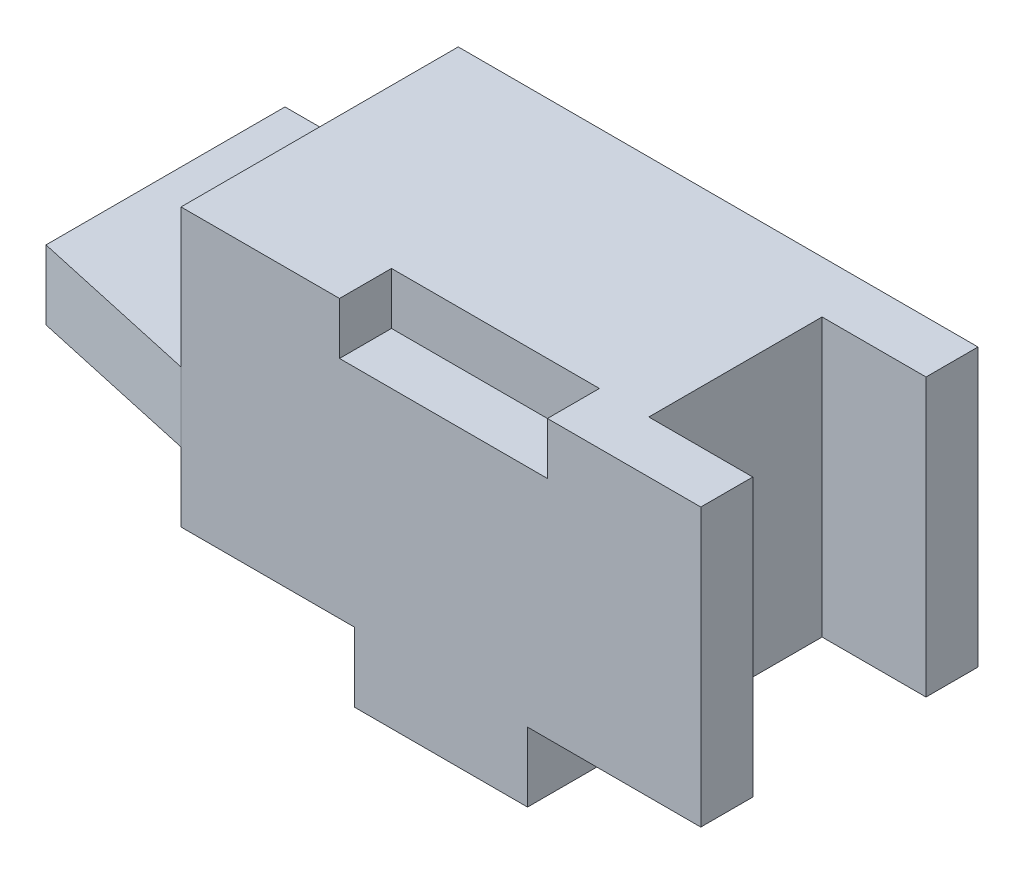
SolidWorks part; units mm, degrees
ref_plane "Спереди" through (0, 0, 0) normal (0, 0, 1) x (1, 0, 0)
ref_plane "Сверху" through (0, 0, 0) normal (0, 1, 0) x (1, 0, 0)
ref_plane "Справа" through (0, 0, 0) normal (1, 0, 0) x (0, 0, -1)
sketch "Эскиз1" plane through (0, 0, 0) normal (0, 0, 1) x (1, 0, 0)
  line L1 (150, -80) -> (0, -80)
  line L2 (150, -80) -> (150, 0)
  line L3 (150, 0) -> (0, 0)
  line L10 (50, -80) -> (50, -100)
  line L11 (50, -100) -> (100, -100)
  line L12 (100, -80) -> (100, -100)
  line L13 (0, -80) -> (0, 0)
  point P0 (0, 0)
  dimension "D1" = 150
  dimension "D2" = 80
  dimension "D7" = 50
  dimension "D8" = 150
  dimension "D9" = 50
  dimension "D10" = 20
extrude "Бобышка-Вытянуть3" add sketch "Эскиз1" along normal blind 80 contours L12 L1 L10 L11 | L13 L1 L2 L3
sketch "Эскиз3" plane through (0, 0, 0) normal (-1, 0, 0) x (0, 0, 1)
  line L0 (0, -80) -> (0, 0) construction
  line L1 (0, -60) -> (80, -60)
  line L2 (0, -60) -> (0, -40)
  line L3 (0, -40) -> (80, -40)
  line L4 (80, -60) -> (80, -40)
  line L5 (80, -80) -> (80, 0) construction
  dimension "D1" = 20
extrude "Бобышка-Вытянуть4" add sketch "Эскиз3" along normal blind 50
sketch "Эскиз4" plane through (0, -60, 0) normal (0, -1, 0) x (1, 0, 0)
  line L0 (-50, 68.9679) -> (0, 80)
  line L1 (-50, 0) -> (-50, 80) construction
  line L2 (-50, 80) -> (0, 80) construction
  line L3 (0, 80) -> (0, 0) construction
  line L4 (0, 80) -> (-50, 80)
  line L5 (-50, 80) -> (-50, 70.9811)
extrude "Вырез-Вытянуть1" cut sketch "Эскиз4" against normal blind 50 and the other way through all
sketch "Эскиз5" plane through (150, 0, 0) normal (1, 0, 0) x (0, 0, -1)
  line L0 (-80, 0) -> (0, 0) construction
  line L1 (-65, 0) -> (-15, 0)
  line L2 (-65, 0) -> (-65, -80)
  line L3 (-65, -80) -> (-15, -80)
  line L4 (-15, 0) -> (-15, -80)
  line L5 (-80, -80) -> (0, -80) construction
  line L6 (-80, -80) -> (-80, 0) construction
  dimension "D1" = 50
  dimension "D2" = 80
  dimension "D3" = 15
extrude "Вырез-Вытянуть2" cut sketch "Эскиз5" against normal blind 30 contours L2 L1 L4 L3
sketch "Эскиз6" plane through (0, 0, 80) normal (0, 0, 1) x (1, 0, 0)
  line L0 (150, 0) -> (0, 0) construction
  line L1 (45.7392, 0) -> (105.7392, 0)
  line L2 (45.7392, 0) -> (45.7392, -15)
  line L3 (45.7392, -15) -> (105.7392, -15)
  line L4 (105.7392, 0) -> (105.7392, -15)
  dimension "D1" = 60
  dimension "D2" = 15
extrude "Вырез-Вытянуть3" cut sketch "Эскиз6" against normal blind 15 contours L2 L1 L4 L3
